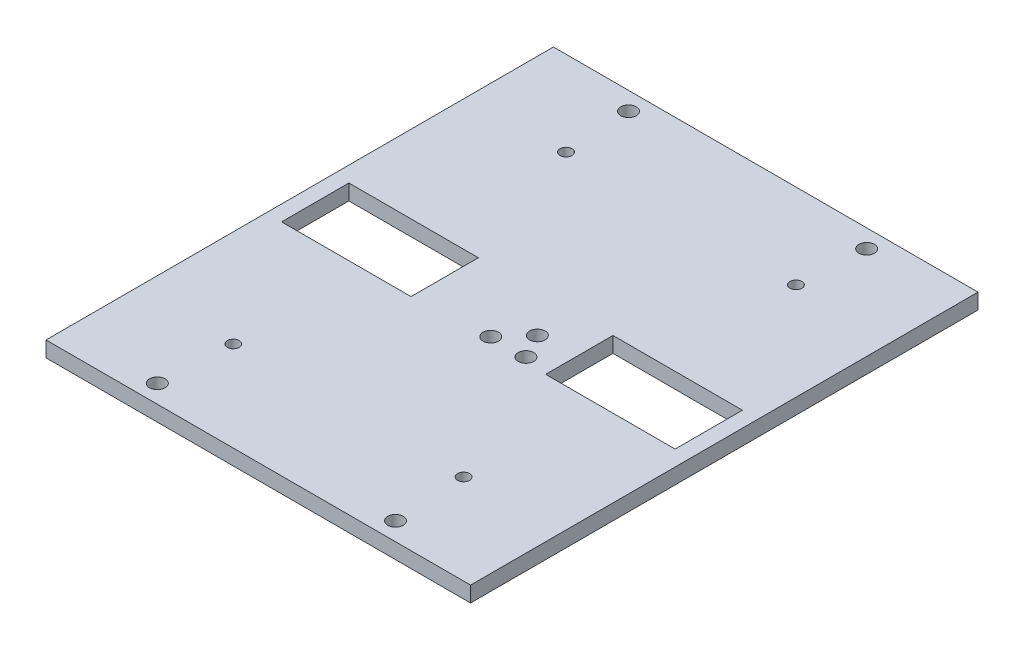
SolidWorks part; units mm, degrees
material "FR4"
ref_plane "Front Plane" through (0, 0, 0) normal (0, 0, 1) x (1, 0, 0)
ref_plane "Top Plane" through (0, 0, 0) normal (0, 1, 0) x (1, 0, 0)
ref_plane "Right Plane" through (0, 0, 0) normal (1, 0, 0) x (0, 0, -1)
sketch "Sketch1" plane through (0, 0, 0) normal (0, 1, 0) x (1, 0, 0)
  line L1 (41, -49) -> (-41, -49)
  line L2 (41, -49) -> (41, 49)
  line L3 (41, 49) -> (-41, 49)
  line L4 (-41, -49) -> (-41, 49)
  line L5 (41, -49) -> (-41, 49) construction
  line L6 (41, 49) -> (-41, -49) construction
  point P0 (0, 0)
  dimension "D1" = 82
  dimension "D2" = 98
extrude "Boss-Extrude1" add sketch "Sketch1" along normal blind 3
hole_wizard "Ø3.0 (3) Diameter Hole1" positions "Sketch4" profile "Sketch2" hole size "Ø3.0" standard "ANSI Metric"
sketch "Sketch4" plane through (0, 0, 0) normal (0, -1, 0) x (-1, 0, 0)
  point P0 (23, -45.5)
  point P2 (-23, -45.5)
  point P4 (-23, 45.5)
  point P6 (23, 45.5)
sketch "Sketch2" plane through (-23, 0, 45.5) normal (1, 0, 0) x (0, 0, -1)
  line L0 (0, 0) -> (0, 30)
  line L1 (0, 30) -> (1.5, 30)
  line L2 (1.5, 30) -> (1.5, 0)
  line L5 (1.5, 0) -> (0, 0)
  line L10 (0, 30) -> (-1.5, 30) construction
  line L11 (0, -6.35) -> (0, 107.95) construction
  dimension "Hole Dia." = 3
  dimension "Hole Depth" = 30
  dimension "Drill Angle" = 180
sketch "Sketch5" plane through (0, 0, 0) normal (0, -1, 0) x (1, 0, 0)
  line L1 (-38, -6.5) -> (-13, -6.5)
  line L2 (-38, -6.5) -> (-38, 6.5)
  line L3 (-38, 6.5) -> (-13, 6.5)
  line L4 (-13, -6.5) -> (-13, 6.5)
  line L5 (13, -6.5) -> (38, -6.5)
  line L6 (13, -6.5) -> (13, 6.5)
  line L7 (13, 6.5) -> (38, 6.5)
  line L8 (38, -6.5) -> (38, 6.5)
extrude "Cut-Extrude1" cut sketch "Sketch5" against normal blind 10
hole_wizard "Ø2.3 (2.3) Diameter Hole1" positions "Sketch7" profile "Sketch6" hole size "Ø2.3" standard "ANSI Metric"
sketch "Sketch7" plane through (0, 3, 0) normal (0, 1, 0) x (1, 0, 0)
  line L0 (0, 0) -> (0, 49) construction
  line L1 (41, 49) -> (-41, 49) construction
  point P0 (-22.245, -31.5907)
  point P2 (22.245, -31.5907)
  point P4 (22.2031, 32.6338)
  point P6 (-22.2031, 32.6338)
sketch "Sketch6" plane through (-22.245, 3, 31.5907) normal (1, 0, 0) x (0, 0, 1)
  line L0 (0, 0) -> (0, 30)
  line L1 (0, 30) -> (1.15, 30)
  line L2 (1.15, 30) -> (1.15, 0)
  line L5 (1.15, 0) -> (0, 0)
  line L10 (0, 30) -> (-1.15, 30) construction
  line L11 (0, -6.35) -> (0, 107.95) construction
  dimension "Hole Dia." = 2.3
  dimension "Hole Depth" = 30
  dimension "Drill Angle" = 180
sketch "Sketch8" plane through (0, 0, 0) normal (0, -1, 0) x (1, 0, 0)
  circle A0 centre (5.7, 0.8) radius 1.5
extrude "Cut-Extrude2" cut sketch "Sketch8" against normal blind 10
hole_wizard "Ø3.0 (3) Diameter Hole2" positions "Sketch10" profile "Sketch9" hole size "Ø3.0" standard "ANSI Metric"
sketch "Sketch10" plane through (0, 0, 0) normal (0, -1, 0) x (-1, 0, 0)
  point P0 (-1.4, -5.5)
  point P2 (-8.2, -5.5)
sketch "Sketch9" plane through (1.4, 0, 5.5) normal (1, 0, 0) x (0, 0, -1)
  line L0 (0, 0) -> (0, 6.5)
  line L1 (0, 6.5) -> (1.5, 6.5)
  line L2 (1.5, 6.5) -> (1.5, 0)
  line L5 (1.5, 0) -> (0, 0)
  line L10 (0, 6.5) -> (-1.5, 6.5) construction
  line L11 (0, -6.35) -> (0, 107.95) construction
  dimension "Hole Dia." = 3
  dimension "Hole Depth" = 6.5
  dimension "Drill Angle" = 180
